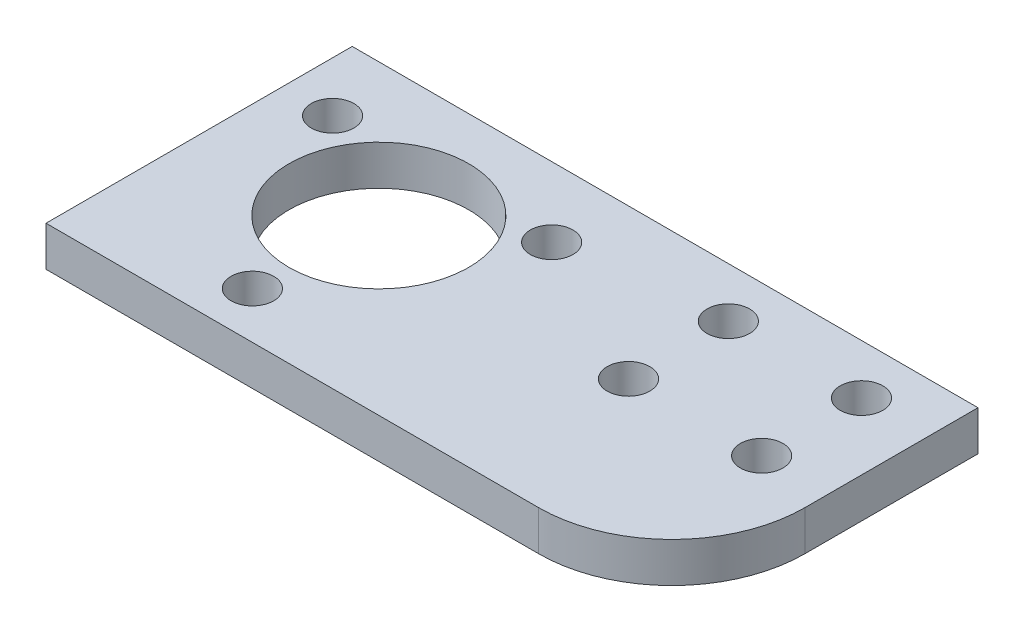
SolidWorks part; units mm, degrees
ref_plane "前视基准面" through (0, 0, 0) normal (0, 0, 1) x (1, 0, 0)
ref_plane "上视基准面" through (0, 0, 0) normal (0, 1, 0) x (1, 0, 0)
ref_plane "右视基准面" through (0, 0, 0) normal (1, 0, 0) x (0, 0, -1)
other "Configuration Table"
sketch "草图1" plane through (0, 0, 0) normal (0, 1, 0) x (1, 0, 0)
  line L1 (-23.5, -11.5) -> (23.5, -11.5)
  line L2 (-23.5, -11.5) -> (-23.5, 11.5)
  line L3 (-23.5, 11.5) -> (23.5, 11.5)
  line L4 (23.5, -11.5) -> (23.5, 11.5)
  line L5 (-23.5, -11.5) -> (23.5, 11.5) construction
  line L6 (-23.5, 11.5) -> (23.5, -11.5) construction
  point P0 (0, 0)
  dimension "D1" = 23
  dimension "D2" = 47
extrude "凸台-拉伸1" add sketch "草图1" along normal blind 3
sketch "草图2" plane through (0, 3, 0) normal (0, 1, 0) x (1, 0, 0)
  line L0 (-23.5, -11.5) -> (23.5, -11.5) construction
  line L5 (-11.5, 1.5) -> (-11.5, -8) construction
  line L6 (-11.5, 1.5) -> (-3.2728, 6.25) construction
  line L7 (-11.5, 1.5) -> (-19.7272, 6.25) construction
  line L8 (23.5, 11.5) -> (-23.5, 11.5) construction
  line L9 (-23.5, 11.5) -> (-23.5, -11.5) construction
  line L10 (13.5, 11.5) -> (13.5, -11.5) construction
  line L11 (18.5, 7.75) -> (18.5, 0.25) construction
  line L12 (23.5, -11.5) -> (23.5, 11.5) construction
  line L13 (8.5, 7.75) -> (8.5, 0.25) construction
  circle A0 centre (-11.5, 1.5) radius 9.5 construction
  circle A1 centre (-19.7272, 6.25) radius 1.6
  circle A2 centre (-11.5, -8) radius 1.6
  circle A3 centre (-3.2728, 6.25) radius 1.6
  circle A4 centre (-11.5, 1.5) radius 6.75
  circle A5 centre (18.5, 7.75) radius 1.6
  circle A6 centre (18.5, 0.25) radius 1.6
  circle A7 centre (8.5, 0.25) radius 1.6
  circle A8 centre (8.5, 7.75) radius 1.6
  point P4 (0, 0)
  dimension "D2" = 19
  dimension "D5" = 3.2
  dimension "D7" = 13.5
  dimension "D8" = 3.2
  dimension "D13" = 3.2
  dimension "D1" = 10
  dimension "D3" = 120
  dimension "D4" = 120
  dimension "D6" = 12
  dimension "D9" = 7.5
  dimension "D10" = 5
  dimension "D11" = 10
  dimension "D12" = 3.75
extrude "切除-拉伸1" cut sketch "草图2" against normal through all contours A4 | A3 | A2 | A1
fillet "圆角1" radius 10 1 edges at (23.5, 1.5, 11.5)
